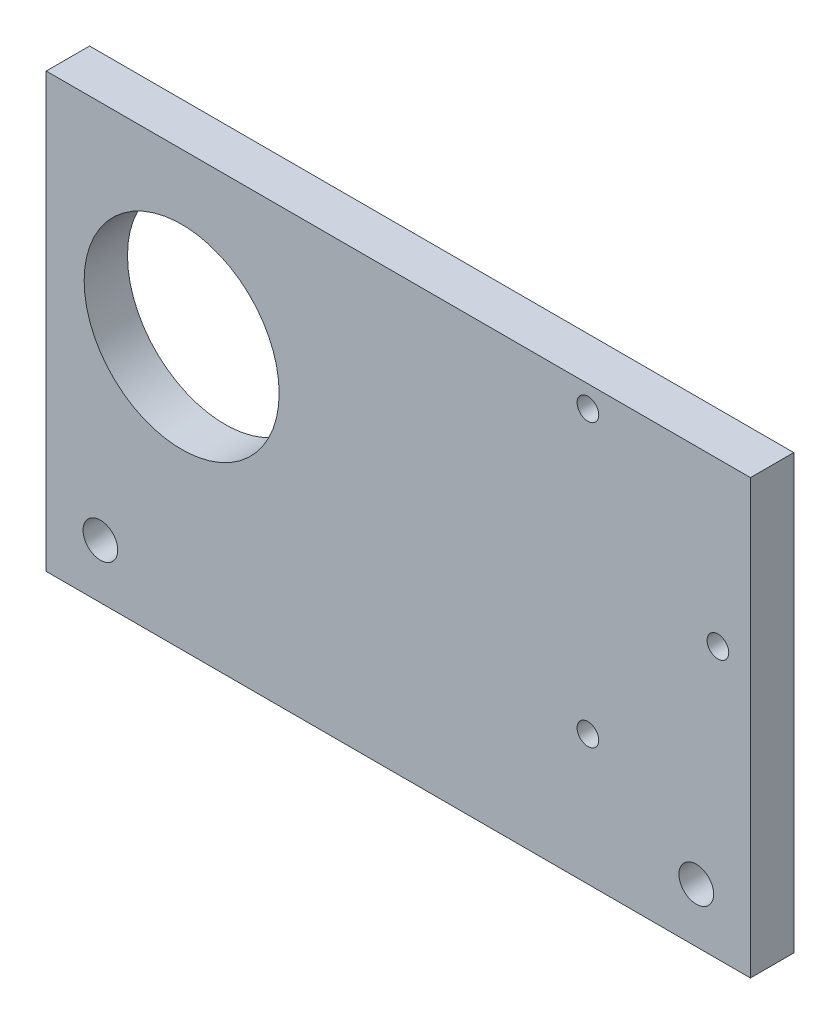
SolidWorks part; units mm, degrees
ref_plane "正面" through (0, 0, 0) normal (0, 0, 1) x (1, 0, 0)
ref_plane "平面" through (0, 0, 0) normal (0, 1, 0) x (1, 0, 0)
ref_plane "右側面" through (0, 0, 0) normal (1, 0, 0) x (0, 0, -1)
sketch "ｽｹｯﾁ1" plane through (0, 0, 0) normal (0, 0, 1) x (1, 0, 0)
  line L1 (0, 0) -> (65, 0)
  line L2 (0, 0) -> (0, 40)
  line L3 (0, 40) -> (65, 40)
  line L4 (65, 0) -> (65, 40)
  circle A0 centre (5, 5) radius 1.6
  circle A1 centre (60, 5) radius 1.6
  circle A3 centre (50, 12) radius 1
  circle A4 centre (62, 25) radius 1
  circle A5 centre (50, 38) radius 1
  circle A6 centre (12.5, 25) radius 9
  dimension "D3" = 5
  dimension "D4" = 5
  dimension "D5" = 5
  dimension "D6" = 15
  dimension "D8" = 13
  dimension "D9" = 13
  dimension "D10" = 12.5
  dimension "D11" = 12
  dimension "D1" = 65
  dimension "D2" = 40
  dimension "D7" = 12
extrude "ﾎﾞｽ - 押し出し1" add sketch "ｽｹｯﾁ1" along normal blind 4
